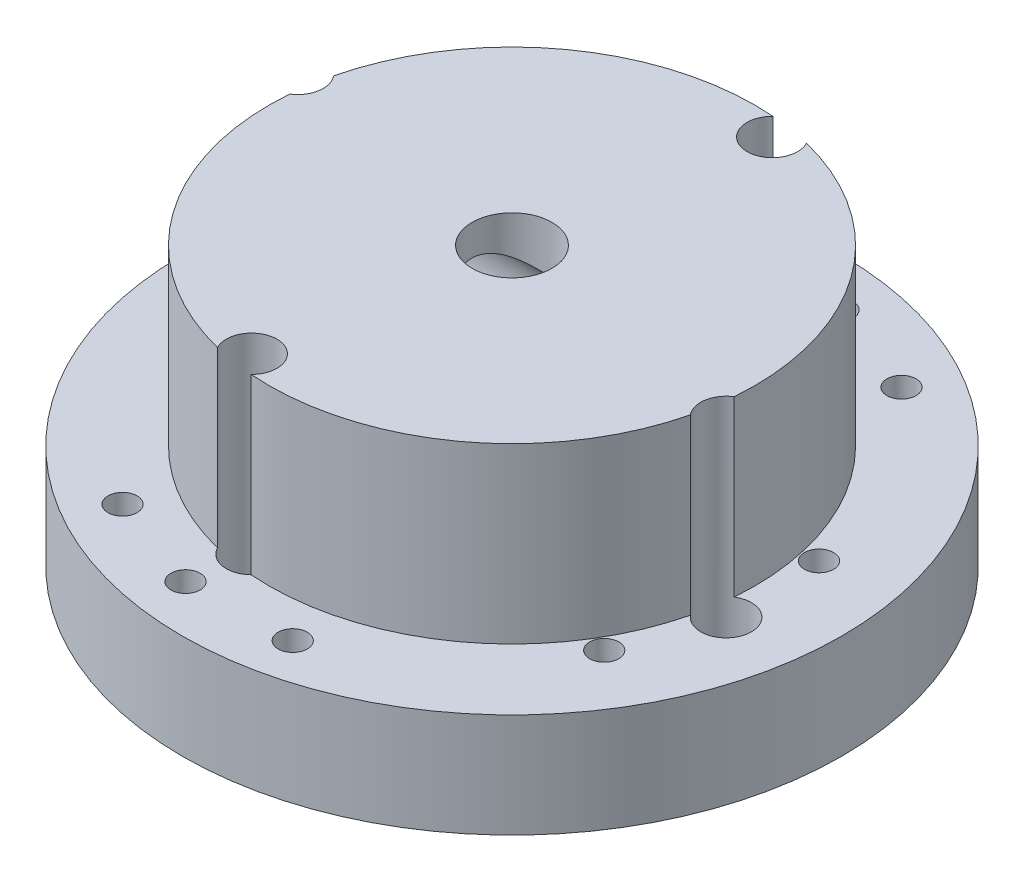
SolidWorks part; units mm, degrees
ref_plane "Front Plane" through (0, 0, 0) normal (0, 0, 1) x (1, 0, 0)
ref_plane "Top Plane" through (0, 0, 0) normal (0, 1, 0) x (1, 0, 0)
ref_plane "Right Plane" through (0, 0, 0) normal (1, 0, 0) x (0, 0, -1)
sketch "Sketch1" plane through (0, 0, 0) normal (0, 1, 0) x (1, 0, 0)
  circle A0 centre (0, 0) radius 12.065
  circle A1 centre (0, 0) radius 9.525
  dimension "D1" = 24.13
  dimension "D2" = 19.05
extrude "Boss-Extrude1" add sketch "Sketch1" along normal blind 3.81
sketch "Sketch2" plane through (0, 0, 0) normal (0, 1, 0) x (1, 0, 0)
  circle A0 centre (0, 0) radius 2.54
  dimension "D1" = 5.08
extrude "Cut-Extrude1" cut sketch "Sketch2" along normal blind 10.16
sketch "Sketch3" plane through (0, 3.81, 0) normal (0, 1, 0) x (1, 0, 0)
  circle A0 centre (0, 0) radius 6.35
  dimension "D1" = 12.7
extrude "Boss-Extrude2" add sketch "Sketch3" along normal blind 1.27
sketch "Sketch5" plane through (0, 5.08, 0) normal (0, 1, 0) x (1, 0, 0)
  circle A1 centre (0, 0) radius 6.35
extrude "Boss-Extrude3" add sketch "Sketch5" along normal blind 5.08
hole_wizard "#4 Clearance Hole1" positions "Sketch9" profile "Sketch10" hole size "#4" standard "ANSI Inch"
sketch "Sketch9" plane through (0, 10.16, 0) normal (0, 1, 0) x (1, 0, 0)
  point P0 (0, 0)
sketch "Sketch10" plane through (0, 10.16, 0) normal (1, 0, 0) x (0, 0, 1)
  line L0 (0, 0) -> (0, 8.382)
  line L1 (0, 8.382) -> (1.4605, 7.5044)
  line L2 (1.4605, 7.5044) -> (1.4605, 0)
  line L5 (1.4605, 0) -> (0, 0)
  line L10 (0, 8.382) -> (-1.4605, 7.5044) construction
  line L11 (0, -6.35) -> (0, 107.95) construction
  dimension "Hole Dia." = 2.921
  dimension "Hole Depth" = 8.382
  dimension "Drill Angle" = 118
ref_plane "Plane1" through (-12.7, 0, 0) normal (1, 0, 0) x (0, 0, -1)
ref_plane "Plane3" through (-12.7, 0, 0) normal (1, 0, 0) x (0, 0, -1)
ref_plane "Plane7" through (-6.35, 0, 0) normal (1, 0, 0) x (0, 0, -1)
sketch "Sketch7" plane through (0, 0, 0) normal (1, 0, 0) x (0, 0, -1)
  line L0 (0, 3.81) -> (0, 0)
  line L1 (12.065, 3.81) -> (-12.065, 3.81) construction
  circle A0 centre (0, 1.905) radius 3.175
ref_plane "Plane9" through (0, 0, 0) normal (1, 0, 0) x (0, 0, -1)
sketch "Sketch11" plane through (0, 10.16, 0) normal (0, 1, 0) x (1, 0, 0)
  line L1 (6.35, 6.35) -> (-6.35, 6.35)
  line L2 (6.35, 6.35) -> (6.35, -6.35)
  line L3 (6.35, -6.35) -> (-6.35, -6.35)
  line L4 (-6.35, 6.35) -> (-6.35, -6.35)
  line L5 (6.35, 6.35) -> (-6.35, -6.35) construction
  line L6 (6.35, -6.35) -> (-6.35, 6.35) construction
  circle A0 centre (0, 0) radius 1.4605 construction
  circle A1 centre (0, 0) radius 1.4605
  circle A2 centre (0, 0) radius 6.35 construction
extrude "Boss-Extrude4" add sketch "Sketch11" against normal up to surface (6.35 mm away) up to face at (0, 3.81, 6.35)
sketch "Sketch12" plane through (0, 0, 0) normal (1, 0, 0) x (0, 0, -1)
  line L0 (6.35, 10.16) -> (-6.35, 10.16) construction
  line L1 (-6.35, 3.81) -> (6.35, 3.81) construction
  line L2 (6.35, 10.16) -> (-6.35, 10.16) construction
  line L3 (-6.35, 3.81) -> (6.35, 3.81) construction
  line L4 (0, 10.16) -> (0, 3.81) construction
  circle A0 centre (0, 6.985) radius 3.175
ref_plane "Plane10" through (0, 0, 0) normal (1, 0, 0) x (0, 0, -1)
sketch "Sketch17" [suppressed] plane through (0, 22.352, 0) normal (0, 1, 0) x (1, 0, 0)
  circle A0 centre (0, 0) radius 1.4732 construction
  circle A1 centre (0, 0) radius 1.4732
extrude "Cut-Extrude4" [suppressed] cut sketch "Sketch17" against normal up to surface (9.652 mm away)
sketch "Sketch18" plane through (0, 10.16, 0) normal (0, 1, 0) x (1, 0, 0)
  circle A0 centre (0, 0) radius 6.35
extrude "Cut-Extrude5" cut sketch "Sketch18" against normal up to surface (6.35 mm away) flip side to cut up to face at (0, 3.81, 0)
sketch "Sketch28" plane through (0, 10.16, 0) normal (0, 1, 0) x (1, 0, 0)
  circle A0 centre (0, 0) radius 6.35 construction
  circle A1 centre (0, 0) radius 6.35
  circle A2 centre (0, 0) radius 8.89
  dimension "D1" = 2.54
extrude "Boss-Extrude5" add sketch "Sketch28" against normal up to surface (6.35 mm away) up to face at (0, 3.81, 6.35)
hole_wizard "#20 (0.161) Diameter Hole3" positions "Sketch26" profile "Sketch27" hole size "#20" standard "ANSI Inch"
sketch "Sketch26" plane through (0, 0, 0) normal (1, 0, 0) x (0, 0, -1)
  point P0 (0, 6.985)
sketch "Sketch27" plane through (0, 6.985, 0) normal (0, 1, 0) x (0, 0, -1)
  line L0 (0, 0) -> (0, 12.065)
  line L1 (0, 12.065) -> (2.0447, 12.065)
  line L2 (2.0447, 12.065) -> (2.0447, 0)
  line L5 (2.0447, 0) -> (0, 0)
  line L11 (0, -6.35) -> (0, 107.95) construction
  dimension "Thru Hole Dia." = 4.0894
  dimension "Thru Hole Depth" = 12.065
sketch "Sketch29" plane through (0, 0, 0) normal (0, -1, 0) x (1, 0, 0)
  circle A0 centre (9.2678, -1.967) radius 0.5334 construction
  circle A1 centre (9.3519, 1.5172) radius 0.5334 construction
  circle A2 centre (8.1705, 4.7961) radius 0.5334 construction
  circle A3 centre (1.7247, 8.1248) radius 0.5334 construction
  circle A4 centre (2.1625, 10.187) radius 0.5334 construction
  circle A5 centre (-1.6677, 10.2796) radius 0.5334 construction
  circle A6 centre (-1.3301, 8.1986) radius 0.5334 construction
  circle A7 centre (-5.2722, 8.9808) radius 0.5334 construction
  circle A8 centre (-4.2049, 7.1628) radius 0.5334 construction
  circle A9 centre (-8.1705, -4.7961) radius 0.5334 construction
  circle A10 centre (-9.3519, -1.5172) radius 0.5334 construction
  circle A11 centre (-9.2678, 1.967) radius 0.5334 construction
  circle A12 centre (9.2678, -1.967) radius 0.5334
  circle A13 centre (9.3519, 1.5172) radius 0.5334
  circle A14 centre (8.1705, 4.7961) radius 0.5334
  circle A15 centre (1.7247, 8.1248) radius 0.5334
  circle A16 centre (2.1625, 10.187) radius 0.5334
  circle A17 centre (-1.6677, 10.2796) radius 0.5334
  circle A18 centre (-1.3301, 8.1986) radius 0.5334
  circle A19 centre (-5.2722, 8.9808) radius 0.5334
  circle A20 centre (-4.2049, 7.1628) radius 0.5334
  circle A21 centre (-8.1705, -4.7961) radius 0.5334
  circle A22 centre (-9.3519, -1.5172) radius 0.5334
  circle A23 centre (-9.2678, 1.967) radius 0.5334
  circle A24 centre (5.2722, -8.9808) radius 0.5334 construction
  circle A25 centre (4.2049, -7.1628) radius 0.5334 construction
  circle A26 centre (1.3301, -8.1986) radius 0.5334 construction
  circle A27 centre (1.6677, -10.2796) radius 0.5334 construction
  circle A28 centre (-2.1625, -10.187) radius 0.5334 construction
  circle A29 centre (-1.7247, -8.1248) radius 0.5334 construction
  circle A30 centre (5.2722, -8.9808) radius 0.5334
  circle A31 centre (4.2049, -7.1628) radius 0.5334
  circle A32 centre (1.3301, -8.1986) radius 0.5334
  circle A33 centre (1.6677, -10.2796) radius 0.5334
  circle A34 centre (-2.1625, -10.187) radius 0.5334
  circle A35 centre (-1.7247, -8.1248) radius 0.5334
extrude "Cut-Extrude6" cut sketch "Sketch29" against normal up to surface (3.81 mm away) up to face at (0, 3.81, 8.89)
sketch "Sketch30" plane through (0, 3.81, 0) normal (0, -1, 0) x (1, 0, 0)
  circle A0 centre (0, 0) radius 2.54 construction
  circle A1 centre (0, 0) radius 1.4605 construction
  circle A2 centre (0, 0) radius 2.54
  circle A3 centre (0, 0) radius 1.4605
extrude "Boss-Extrude6" add sketch "Sketch30" along normal blind 1.524
sketch "Sketch31" plane through (0, 2.286, 0) normal (0, -1, 0) x (1, 0, 0)
  circle A1 centre (0, 0) radius 2.54
  circle A2 centre (0, 0) radius 2.54
  dimension "D1" = 0
extrude "Boss-Extrude7" add sketch "Sketch31" along normal blind 1.27
sketch "Sketch32" plane through (0, 0, 0) normal (0, -1, 0) x (1, 0, 0)
  circle A0 centre (-1.3301, 8.1986) radius 0.5334 construction
  circle A1 centre (9.3519, 1.5172) radius 0.5334 construction
  circle A2 centre (-9.3519, -1.5172) radius 0.5334 construction
  circle A3 centre (1.3301, -8.1986) radius 0.5334 construction
  circle A4 centre (-1.3301, 8.1986) radius 0.5334 construction
  circle A5 centre (9.3519, 1.5172) radius 0.5334 construction
  circle A6 centre (-9.3519, -1.5172) radius 0.5334 construction
  circle A7 centre (1.3301, -8.1986) radius 0.5334 construction
  circle A8 centre (-1.3301, 8.1986) radius 0.9144
  circle A9 centre (9.3519, 1.5172) radius 0.9144
  circle A10 centre (-9.3519, -1.5172) radius 0.9144
  circle A11 centre (1.3301, -8.1986) radius 0.9144
  dimension "D1" = 0.381
extrude "Cut-Extrude7" cut sketch "Sketch32" against normal through all
sketch "Sketch33" plane through (0, 0, 0) normal (0, -1, 0) x (1, 0, 0)
  circle A0 centre (0, 0) radius 135.89
  circle A1 centre (0, 0) radius 2.54 construction
  circle A2 centre (0, 0) radius 2.54
  circle A3 centre (0, 0) radius 2.75
  circle M19 centre (0, 0) radius 2.54
extrude "Cut-Extrude8" cut sketch "Sketch33" against normal up to surface (1.016 mm away) contours A3 M19 up to face at (0, 1.016, -2.54)
hole_wizard "CSK for #0 Flat Head Machine Screw (100)1" positions "3DSketch1" profile "Sketch34" countersink size "#0" standard "ANSI Inch"
sketch3d "3DSketch1"
  line L0 (1.3301, 10.16, -8.1986) -> (1.3301, 3.81, -8.1986) construction
  line L1 (9.3519, 10.16, 1.5172) -> (9.3519, 3.81, 1.5172) construction
  line L2 (-1.3301, 10.16, 8.1986) -> (-1.3301, 3.81, 8.1986) construction
  line L3 (-9.3519, 10.16, -1.5172) -> (-9.3519, 3.81, -1.5172) construction
  point P2 (1.3301, 0, -8.1986)
  point P6 (9.3519, 0, 1.5172)
  point P10 (-1.3301, 0, 8.1986)
  point P14 (-9.3519, 0, -1.5172)
sketch "Sketch34" plane through (1.3301, 0, -8.1986) normal (1, 0, 0) x (0, 0, -1)
  line L0 (0, 0) -> (0, 10.7161)
  line L1 (0, 10.7161) -> (0.9271, 10.159)
  line L2 (0.9271, 10.159) -> (0.9271, 0.4902)
  line L3 (0.9271, 0.4902) -> (1.5113, 0)
  line L5 (1.5113, 0) -> (0, 0)
  line L6 (-0.9271, 0.4902) -> (-1.5113, 0) construction
  line L10 (0, 10.7161) -> (-0.9271, 10.159) construction
  line L11 (0, -6.35) -> (0, 107.95) construction
  dimension "Hole Dia." = 1.8542
  dimension "Hole Depth" = 10.159
  dimension "Near C'Sink Dia." = 3.0226
  dimension "Near C'Sink Angle" = 100
  dimension "Drill Angle" = 118
